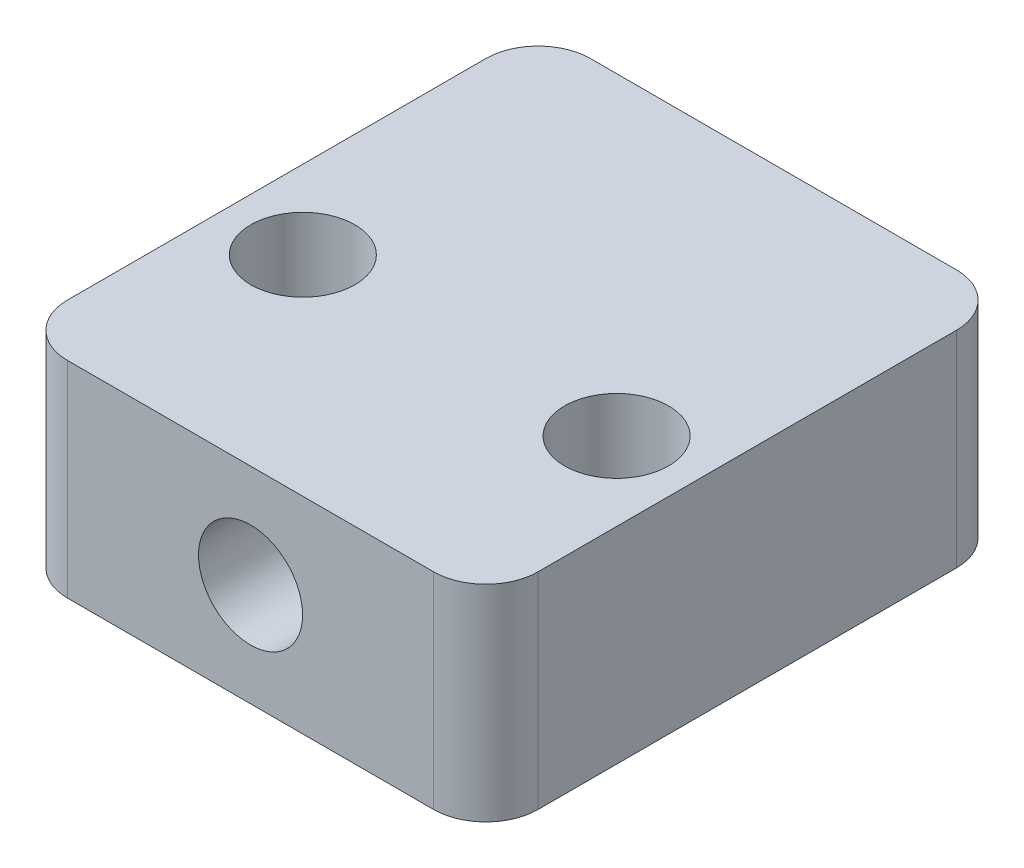
SolidWorks part; units mm, degrees
ref_plane "Front Plane" through (0, 0, 0) normal (0, 0, 1) x (1, 0, 0)
ref_plane "Top Plane" through (0, 0, 0) normal (0, 1, 0) x (1, 0, 0)
ref_plane "Right Plane" through (0, 0, 0) normal (1, 0, 0) x (0, 0, -1)
sketch "Sketch1" plane through (0, 0, 0) normal (0, 1, 0) x (1, 0, 0)
  line L0 (0, 0) -> (0, -2.54) construction
  line L5 (-11.43, -12.7) -> (11.43, -12.7)
  line L6 (-11.43, -12.7) -> (-11.43, 12.7)
  line L12 (-11.43, 12.7) -> (11.43, 12.7)
  line L13 (11.43, -12.7) -> (11.43, 12.7)
  line L14 (-11.43, -12.7) -> (11.43, 12.7) construction
  line L15 (-11.43, 12.7) -> (11.43, -12.7) construction
  line L16 (-7.62, -2.54) -> (7.62, -2.54) construction
  circle A2 centre (-7.62, -2.54) radius 2.5273
  circle A3 centre (7.62, -2.54) radius 2.5273
  point P0 (0, 0)
  point P10 (0, -2.54)
  dimension "D3" = 2.54
  dimension "D4" = 5.0546
  dimension "D5" = 22.86
  dimension "D1" = 25.4
  dimension "D2" = 15.24
extrude "Boss-Extrude1" add sketch "Sketch1" along normal blind 10
fillet "Fillet1" radius 2.54 4 edges at (11.43, 5, 12.7) (-11.43, 5, -12.7) (11.43, 5, -12.7) (-11.43, 5, 12.7)
sketch "Sketch4" plane through (0, 0, 12.7) normal (0, 0, -1) x (-1, 0, 0)
  line L0 (0, 0) -> (0, 10) construction
  line L2 (-8.89, 10) -> (8.89, 10) construction
  circle A0 centre (0, 5) radius 2.5273
  dimension "D1" = 5.0546
extrude "Cut-Extrude1" cut sketch "Sketch4" along normal through all contours A0 L0 | L0 A0
